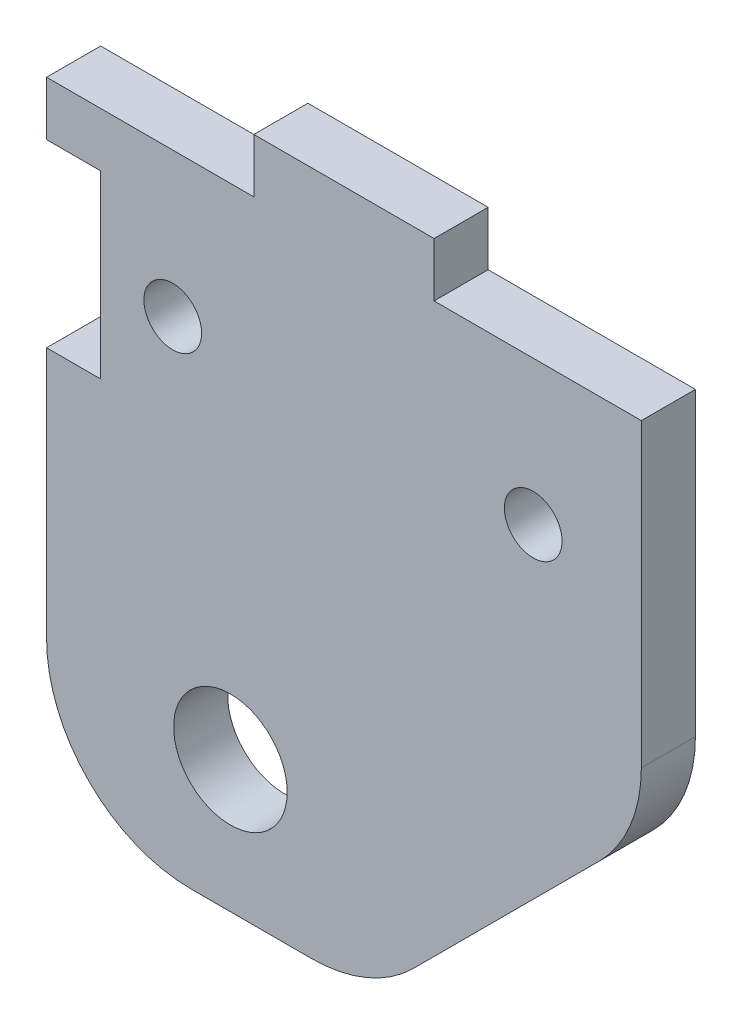
SolidWorks part; units mm, degrees
material "MDF"
ref_plane "Plano frontal" through (0, 0, 0) normal (0, 0, 1) x (1, 0, 0)
ref_plane "Plano superior" through (0, 0, 0) normal (0, 1, 0) x (1, 0, 0)
ref_plane "Plano direito" through (0, 0, 0) normal (1, 0, 0) x (0, 0, -1)
sketch "Esboço1" plane through (0, 0, 0) normal (0, 0, 1) x (1, 0, 0)
  line L5 (0, 0) -> (33, 0)
  line L10 (0.4185, -29.7634) -> (4.2751, -47.9071) construction
  line L11 (4.2751, -47.9071) -> (9.3614, -46.8259) construction
  line L12 (9.3614, -46.8259) -> (10.2, -27.6843) construction
  line L13 (10.2, -27.6843) -> (0.4185, -29.7634) construction
  line L14 (33, 0) -> (33, -35)
  line L15 (33, -35) -> (0, -35)
  line L16 (0, -35) -> (0, 0)
  line L17 (16.5, 0) -> (16.5, -35) construction
  line L18 (10.2, -27.6843) -> (4.2751, -47.9071) construction
  line L19 (10.2, -27.6843) -> (3.1289, -34.7554) construction
  line L20 (3.1289, -34.7554) -> (16.2451, -47.8715) construction
  line L21 (16.2451, -47.8715) -> (19.922, -44.1945) construction
  line L22 (7, -8) -> (4.2751, -47.9071) construction
  line L25 (7, -8) -> (27, -8) construction
  line L47 (21.5, 3) -> (11.5, 3)
  line L48 (21.5, 3) -> (21.5, 0)
  line L49 (21.5, 0) -> (11.5, 0)
  line L50 (11.5, 3) -> (11.5, 0)
  line L51 (16.5, 0) -> (16.5, 3) construction
  line L52 (21.5, 1.5) -> (11.5, 1.5) construction
  line L54 (3, -13) -> (0, -13)
  line L56 (3, -13) -> (3, -3)
  line L60 (3, -3) -> (0, -3)
  line L61 (0, -13) -> (0, -3)
  line L62 (3, -13) -> (0, -3) construction
  line L63 (3, -3) -> (0, -13) construction
  circle A0 centre (10.2, -27.6843) radius 3.15
  circle A1 centre (10.2, -27.6843) radius 22.8 construction
  circle A3 centre (27, -8) radius 1.6
  circle A4 centre (7, -8) radius 1.6
  circle A15 centre (27, -8) radius 3 construction
  circle A16 centre (10.2, -27.6843) radius 10 construction
  point P5 (33, -27.6843)
  point P8 (1.5, -8)
  point P25 (13.35, -27.6843)
  point P31 (16.5, 1.5)
  dimension "D3" = 6.3
  dimension "D6" = 10
  dimension "D11" = 10
  dimension "D19" = 3
  dimension "D18" = 8
  dimension "D10" = 3
  dimension "D21" = 6
  dimension "D23" = 20
  dimension "D15" = 6
  dimension "D13" = 3.2
  dimension "D4" = 19.16
  dimension "D5" = 5.2
  dimension "D7" = 12
  dimension "D8" = 40
  dimension "D9" = 10.2
  dimension "D12" = 45
  dimension "D14" = 8
  dimension "D16" = 7
  dimension "D17" = 20
  dimension "D20" = 10
  dimension "D22" = 35
extrude "Ressalto-extrusão1" add sketch "Esboço1" along normal blind 3
chamfer "Chanfro2" distance 15 angle 45 1 edges at (33, -35, 1.5)
fillet "Filete2" radius 8 3 edges at (0, -35, 1.5) (18, -35, 1.5) (33, -20, 1.5)
